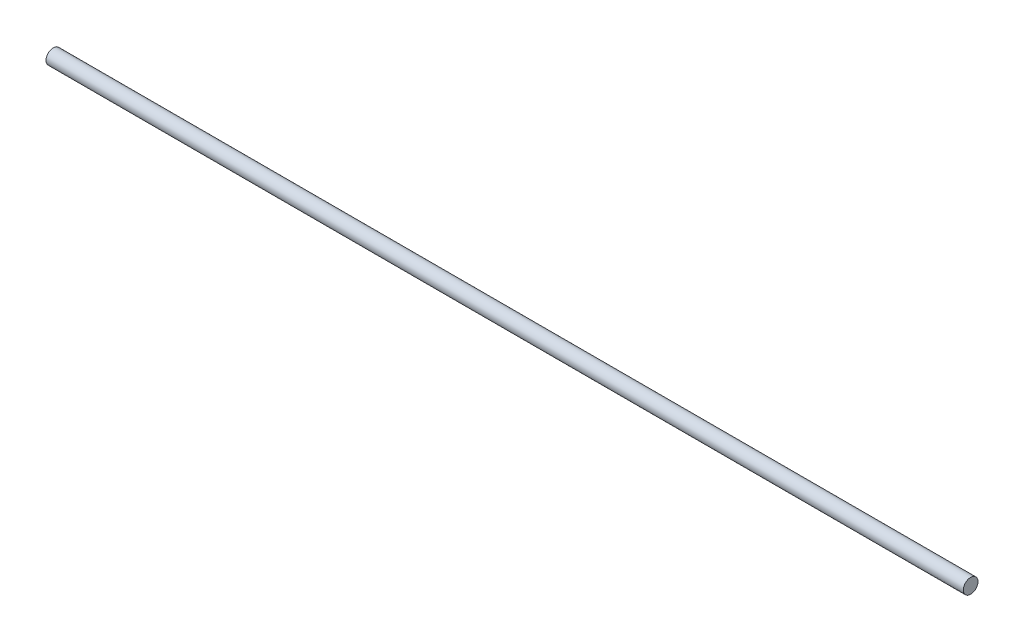
SolidWorks part; units mm, degrees
ref_plane "Front Plane" through (0, 0, 0) normal (0, 0, 1) x (1, 0, 0)
ref_plane "Top Plane" through (0, 0, 0) normal (0, 1, 0) x (1, 0, 0)
ref_plane "Right Plane" through (0, 0, 0) normal (1, 0, 0) x (0, 0, -1)
sketch "Sketch1" plane through (0, 0, 0) normal (1, 0, 0) x (0, 0, -1)
  circle A0 centre (0, 0) radius 12
extrude "Boss-Extrude1" add sketch "Sketch1" along normal blind 1500
